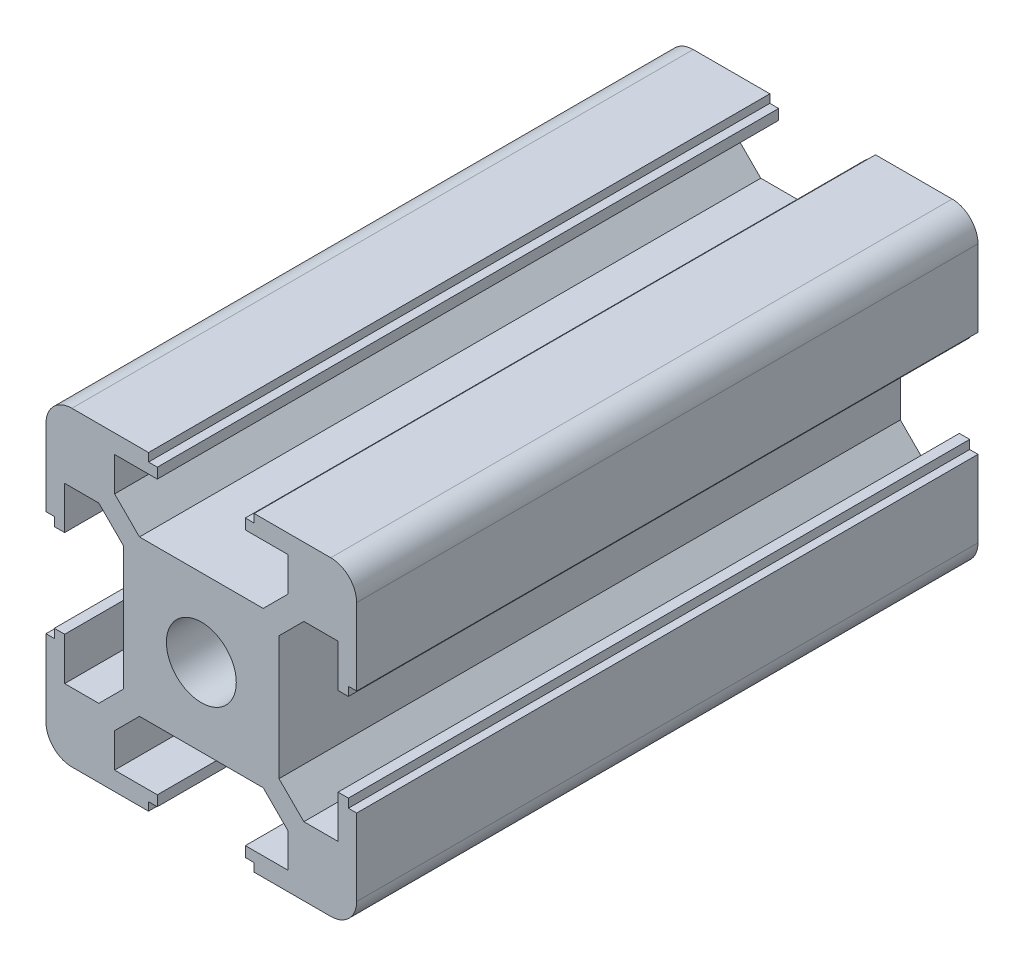
SolidWorks part; units mm, degrees
ref_plane "Front Plane" through (0, 0, 0) normal (0, 0, 1) x (1, 0, 0)
ref_plane "Top Plane" through (0, 0, 0) normal (0, 1, 0) x (1, 0, 0)
ref_plane "Right Plane" through (0, 0, 0) normal (1, 0, 0) x (0, 0, -1)
sketch "Sketch1" plane through (0, 0, 0) normal (0, 0, 1) x (1, 0, 0)
  line L1 (-15, -15) -> (15, -15)
  line L2 (-15, -15) -> (-15, 15)
  line L3 (-15, 15) -> (15, 15)
  line L4 (15, -15) -> (15, 15)
  line L5 (-15, -15) -> (15, 15) construction
  line L6 (-15, 15) -> (15, -15) construction
  point P0 (0, 0)
  dimension "D1" = 30
  dimension "D2" = 30
extrude "Boss-Extrude1" add sketch "Sketch1" along normal mid plane 60
sketch "Sketch2" plane through (0, 0, 30) normal (0, 0, 1) x (1, 0, 0)
  circle A0 centre (0, 0) radius 3.375
  dimension "D1" = 6.75
extrude "Cut-Extrude1" cut sketch "Sketch2" against normal through all
cosmetic thread "Cosmetic Thread1" parameters "D1"=12, "D2"=8
cosmetic thread "Cosmetic Thread2" parameters "D1"=12, "D2"=8
fillet "Fillet1" radius 2.5 4 edges at (15, -15, 0) (-15, -15, 0) (15, 15, 0) (-15, 15, 0)
sketch "Sketch3" plane through (0, 0, 30) normal (0, 0, 1) x (1, 0, 0)
  line L0 (0, -1000) -> (0, 49000) construction
  line L1 (0, 15) -> (-5.1, 15)
  line L2 (12.5, 15) -> (-12.5, 15) construction
  line L3 (-5.1, 15) -> (-5.1, 14.2)
  line L4 (-5.1, 14.2) -> (-4.25, 14.2)
  line L5 (-4.25, 14.2) -> (-4.25, 13.2)
  line L6 (-4.25, 13.2) -> (-8.375, 13.2)
  line L7 (-8.375, 13.2) -> (-8.375, 9.9)
  line L8 (-8.375, 9.9) -> (-5.975, 7.5)
  line L9 (-5.975, 7.5) -> (0, 7.5)
  line L10 (0, 7.5) -> (0, 15)
  dimension "D1" = 5.1
  dimension "D2" = 4.25
  dimension "D3" = 1.8
  dimension "D4" = 1
  dimension "D5" = 3.3
  dimension "D6" = 8.375
  dimension "D7" = 135
  dimension "D8" = 7.5
extrude "Cut-Extrude2" cut sketch "Sketch3" against normal through all
mirror "Mirror1" about plane through (0, 0, 0) normal (1, 0, 0) of "Cut-Extrude2"
pattern_circular "CirPattern1" count 4 over 360 about axis through (0, 0, 0) along (0, 0, 1) of "Mirror1", "Cut-Extrude2"
